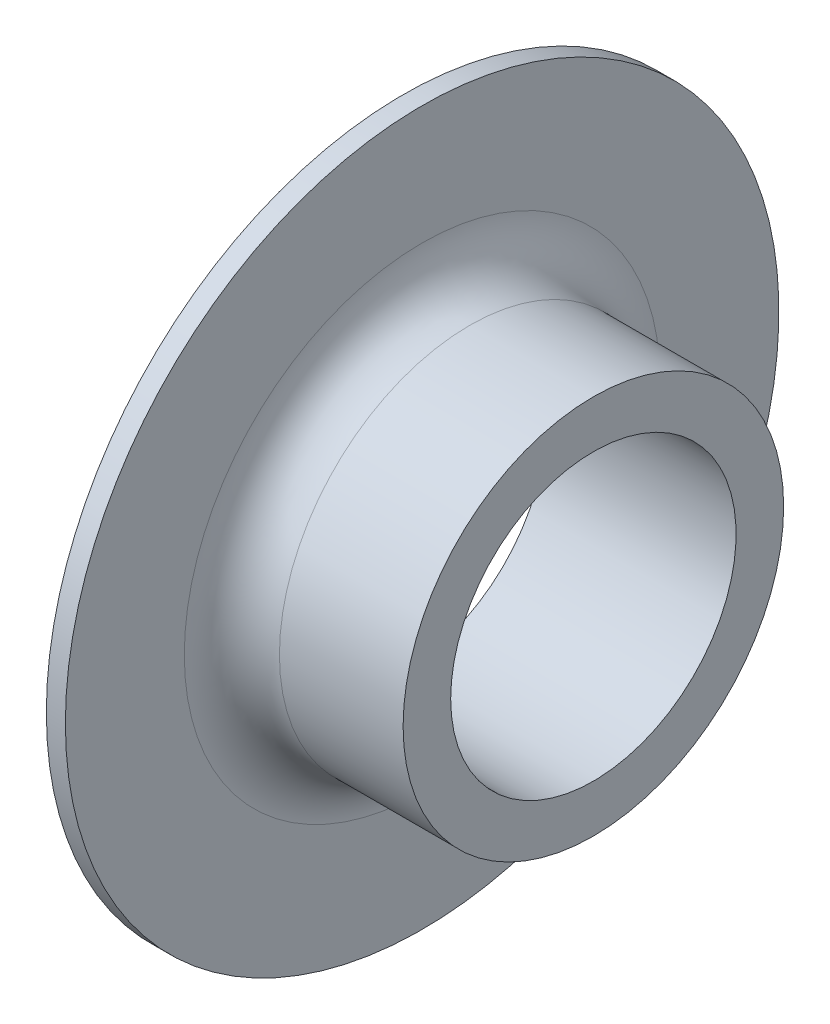
SolidWorks part; units mm, degrees
ref_plane "Ön Düzlem" through (0, 0, 0) normal (0, 0, 1) x (1, 0, 0)
ref_plane "Üst Düzlem" through (0, 0, 0) normal (0, 1, 0) x (1, 0, 0)
ref_plane "Sağ Düzlem" through (0, 0, 0) normal (1, 0, 0) x (0, 0, -1)
sketch "Çizim1" plane through (0, 0, 0) normal (0, 0, 1) x (1, 0, 0)
  line L0 (0, 0) -> (50.8524, 0) construction
  line L1 (0, 14.8791) -> (0, 37.5)
  line L2 (0, 37.5) -> (2, 37.5)
  line L3 (2, 37.5) -> (2, 20)
  line L4 (2, 20) -> (20, 20)
  line L5 (20, 20) -> (20, 15)
  line L6 (20, 15) -> (0, 15)
  line L7 (0, 15) -> (0, 14.8791)
  dimension "D1" = 75
  dimension "D2" = 2
  dimension "D3" = 5
  dimension "D4" = 20
  dimension "D5" = 30
revolve "Döndür1" add sketch "Çizim1" angle 360 about L0
fillet "Radyus1" radius 5 1 edges at (2, 0, 20)
